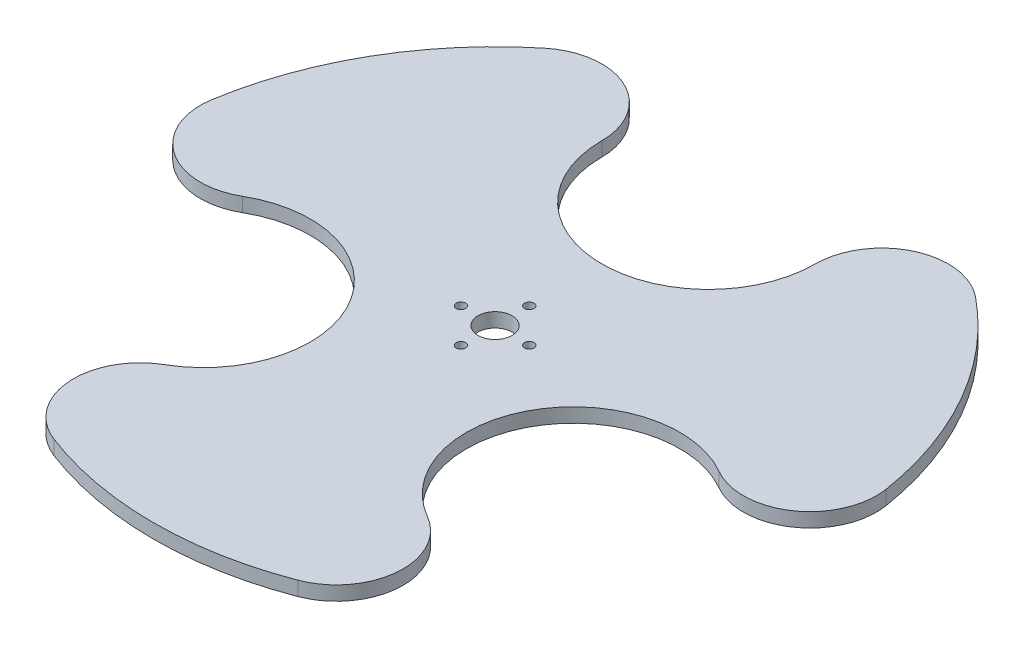
SolidWorks part; units mm, degrees
ref_plane "前基準面" through (0, 0, 0) normal (0, 0, 1) x (1, 0, 0)
ref_plane "上基準面" through (0, 0, 0) normal (0, 1, 0) x (1, 0, 0)
ref_plane "右基準面" through (0, 0, 0) normal (1, 0, 0) x (0, 0, -1)
sketch "草圖1" plane through (0, 0, 0) normal (0, 1, 0) x (1, 0, 0)
  line L2 (0, 75) -> (0, 0) construction
  line L3 (-64.9519, -37.5) -> (0, 0) construction
  line L4 (-28.5, 28.5) -> (28.5, 28.5) construction
  line L5 (-28.5, 28.5) -> (-28.5, -28.5) construction
  line L6 (-28.5, -28.5) -> (28.5, -28.5) construction
  line L7 (28.5, 28.5) -> (28.5, -28.5) construction
  line L8 (0, 0) -> (64.9519, -37.5) construction
  arc A20 (-75.6377, 93.1608) -> (-118.4985, 18.9238) centre (0, 0) ccw
  arc A21 (-37.5, 75) -> (37.5, 75) centre (0, 75) ccw
  circle A24 centre (0, 0) radius 6
  arc A25 (83.7019, -5.024) -> (46.2019, -69.976) centre (64.9519, -37.5) ccw
  arc A26 (-46.2019, -69.976) -> (-83.7019, -5.024) centre (-64.9519, -37.5) ccw
  arc A27 (118.4985, 18.9238) -> (75.6377, 93.1608) centre (0, 0) ccw
  arc A28 (-42.8608, -112.0846) -> (42.8608, -112.0846) centre (0, 0) ccw
  arc A29 (-75.6377, 93.1608) -> (-37.5, 75) centre (-60.8929, 75) cw
  arc A30 (75.6377, 93.1608) -> (37.5, 75) centre (60.8929, 75) ccw
  arc A31 (118.4985, 18.9238) -> (83.7019, -5.024) centre (95.3983, 15.2348) cw
  arc A32 (42.8608, -112.0846) -> (46.2019, -69.976) centre (34.5055, -90.2348) ccw
  arc A33 (-42.8608, -112.0846) -> (-46.2019, -69.976) centre (-34.5055, -90.2348) cw
  arc A34 (-118.4985, 18.9238) -> (-83.7019, -5.024) centre (-95.3983, 15.2348) ccw
  point P16 (0, 28.5)
  point P18 (-28.5, 0)
  dimension "D1" = 75
  dimension "D2" = 240
  dimension "D3" = 75
  dimension "D4" = 12
  dimension "D6" = 3
  dimension "D5" = 57
extrude "填料-伸長1" add sketch "草圖1" against normal blind 5
sketch "草圖2" plane through (0, 0, 0) normal (0, 1, 0) x (1, 0, 0)
  line L0 (-12, 0) -> (12, 0)
  line L1 (0, -12) -> (0, 12)
  point P4 (0, 0)
  point P5 (0, 0)
  dimension "D1" = 24
hole_wizard "M4 螺紋孔1" positions "草圖3" profile "草圖4" tap size "M4" standard "ISO" end condition through all
sketch "草圖3" plane through (0, 0, 0) normal (0, 1, 0) x (1, 0, 0)
  point P0 (0, 12)
  point P3 (12, 0)
  point P6 (0, -12)
  point P9 (-12, 0)
sketch "草圖4" plane through (0, 0, -12) normal (1, 0, 0) x (0, 0, 1)
  line L0 (0, 0) -> (0, 5)
  line L1 (0, 5) -> (1.65, 5)
  line L2 (1.65, 5) -> (1.65, 0)
  line L5 (1.65, 0) -> (0, 0)
  line L11 (0, -6.35) -> (0, 107.95) construction
  dimension "貫穿螺孔鑽直徑" = 3.3
  dimension "貫穿螺孔鑽深度" = 5
cosmetic thread "鑽孔螺紋1" parameters "D2"=4
cosmetic thread "鑽孔螺紋2" parameters "D2"=4
cosmetic thread "鑽孔螺紋3" parameters "D2"=4
cosmetic thread "鑽孔螺紋4" parameters "D2"=4
